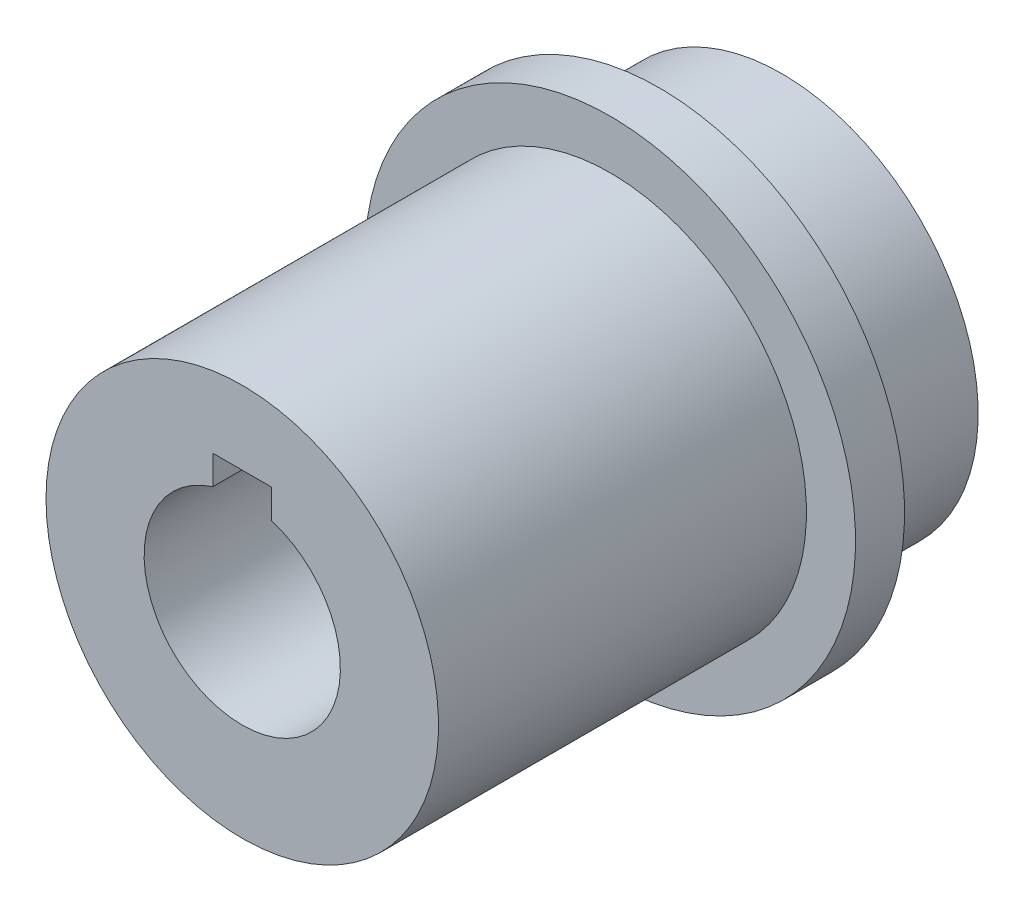
SolidWorks part; units mm, degrees
material "ASTM A36 Steel"
ref_plane "Front Plane" through (0, 0, 0) normal (0, 0, 1) x (1, 0, 0)
ref_plane "Top Plane" through (0, 0, 0) normal (0, 1, 0) x (1, 0, 0)
ref_plane "Right Plane" through (0, 0, 0) normal (1, 0, 0) x (0, 0, -1)
sketch "Sketch1" plane through (0, 0, 0) normal (0, 0, 1) x (1, 0, 0)
  circle A0 centre (0, 0) radius 20
  circle A1 centre (0, 0) radius 40
  dimension "D1" = 40
  dimension "D2" = 80
extrude "Boss-Extrude1" add sketch "Sketch1" along normal blind 110
ref_plane "Plane1" through (0, 0, 25) normal (0, 0, 1) x (1, 0, 0)
sketch "Sketch2" plane through (0, 0, 25) normal (0, 0, 1) x (1, 0, 0)
  circle A0 centre (0, 0) radius 50
  circle A1 centre (0, 0) radius 20
  dimension "D1" = 100
  dimension "D2" = 40
extrude "Boss-Extrude2" add sketch "Sketch2" along normal blind 10
sketch "Sketch3" plane through (0, 0, 0) normal (0, 0, -1) x (-1, 0, 0)
  line L1 (-6, 25) -> (6, 25)
  line L2 (-6, 25) -> (-6, 10.3765)
  line L3 (-6, 10.3765) -> (6, 10.3765)
  line L4 (6, 25) -> (6, 10.3765)
  point P4 (0, 25)
  dimension "D1" = 12
  dimension "D2" = 25
extrude "Cut-Extrude1" cut sketch "Sketch3" against normal through all
